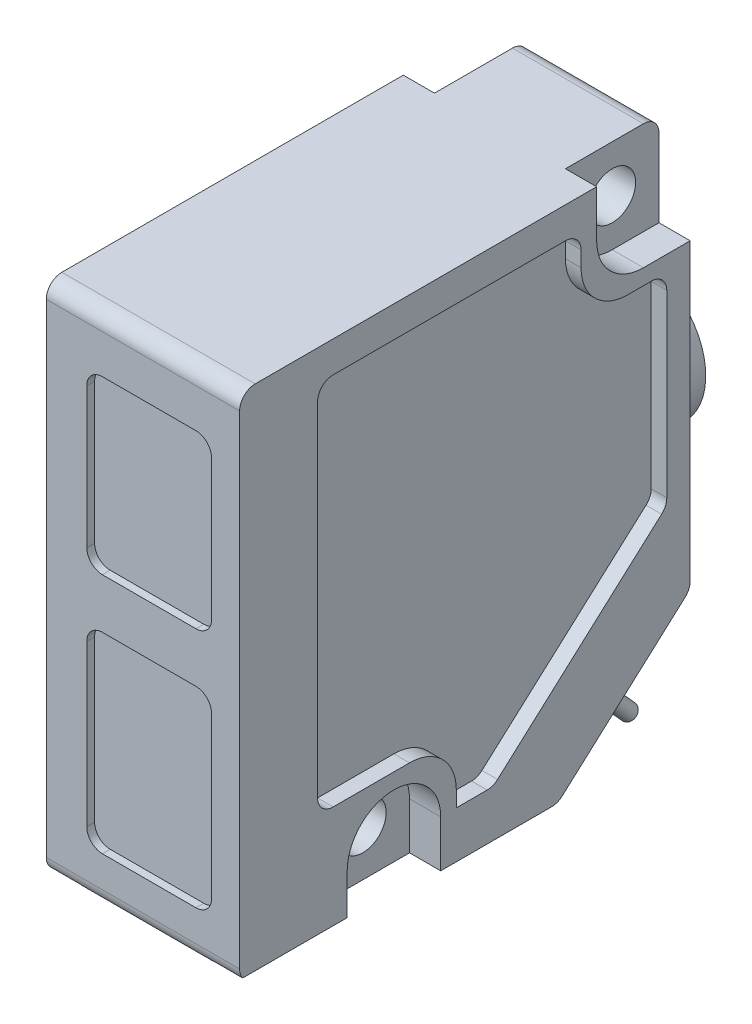
SolidWorks part; units mm, degrees
material "ABS"
ref_plane "Front Plane" through (0, 0, 0) normal (0, 0, 1) x (1, 0, 0)
ref_plane "Top Plane" through (0, 0, 0) normal (0, 1, 0) x (1, 0, 0)
ref_plane "Right Plane" through (0, 0, 0) normal (1, 0, 0) x (0, 0, -1)
sketch "Sketch1" plane through (0, 0, 0) normal (1, 0, 0) x (0, 0, -1)
  line L0 (1, 0) -> (27.9, 0)
  line L1 (28.9, -1) -> (28.9, -24.9046)
  line L2 (28.569, -25.6479) -> (20.6852, -32.7433)
  line L3 (20.0163, -33) -> (1, -33)
  line L4 (0, -32) -> (0, -1)
  arc A0 (1, -33) -> (0, -32) centre (1, -32) cw
  arc A1 (27.9, 0) -> (28.9, -1) centre (27.9, -1) cw
  arc A2 (1, 0) -> (0, -1) centre (1, -1) ccw
  arc A3 (28.9, -24.9046) -> (28.569, -25.6479) centre (27.9, -24.9046) cw
  arc A4 (20.6852, -32.7433) -> (20.0163, -33) centre (20.0163, -32) cw
  point P8 (0, -33)
  point P11 (28.9, 0)
  point P14 (0, 0)
  point P17 (28.9, -25.35)
  point P20 (20.4, -33)
  dimension "D5" = 1
  dimension "D6" = 1
  dimension "D1" = 33
  dimension "D2" = 28.9
  dimension "D3" = 20.4
  dimension "D4" = 7.65
extrude "Boss-Extrude1" add sketch "Sketch1" along normal blind 12.4
sketch "Sketch2" plane through (12.4, 0, 0) normal (1, 0, 0) x (0, 0, -1)
  line L0 (27.9, 0) -> (1, 0) construction
  line L1 (28.9, -24.9046) -> (28.9, -1) construction
  line L2 (1, -33) -> (20.0163, -33) construction
  line L3 (0, -1) -> (0, -32) construction
  circle A0 centre (25.9, -3) radius 1.5
  circle A1 centre (9.9, -30) radius 1.5
  dimension "D1" = 3
  dimension "D2" = 3
  dimension "D3" = 3
  dimension "D4" = 3
  dimension "D5" = 9.9
  dimension "D6" = 27
  dimension "D7" = 31.3847
  dimension "D8" = 16
extrude "Cut-Extrude1" cut sketch "Sketch2" against normal through all
sketch "Sketch3" plane through (12.4, 0, 0) normal (1, 0, 0) x (0, 0, -1)
  line L0 (27.9, 0) -> (1, 0) construction
  line L5 (6.9, -30) -> (6.9, -32.6022)
  line L6 (1, -33) -> (20.0163, -33) construction
  line L7 (12.9, -30) -> (12.9, -33)
  line L8 (6.9, -33) -> (12.9, -33)
  line L9 (22.9, 0) -> (28.9, 0)
  line L10 (22.9, 0) -> (22.9, -3)
  line L11 (25.9, -6) -> (28.9, -6)
  line L12 (28.9, 0) -> (28.9, -6)
  line L13 (28.9, -24.9046) -> (28.9, -1) construction
  line L15 (6.9, -33) -> (0, -33)
  line L17 (6.9, -32.6022) -> (0, -32.6022)
  line L18 (0, -33) -> (0, -32.6022)
  arc A1 (12.9, -30) -> (6.9, -30) centre (9.9, -30) ccw
  arc A2 (22.9, -3) -> (25.9, -6) centre (25.9, -3) ccw
  point P18 (22.9, -6)
  dimension "D3" = 3
  dimension "D4" = 6
  dimension "D1" = 6
  dimension "D2" = 6
  dimension "D5" = 0.3978
  dimension "D6" = 6.9
extrude "Cut-Extrude2" cut sketch "Sketch3" against normal blind 2
sketch "Sketch4" plane through (0, 0, 0) normal (-1, 0, 0) x (0, 0, 1)
  line L0 (-12.9, -30) -> (-12.9, -33)
  line L1 (-28.9, 0) -> (-22.9, 0)
  line L2 (-28.9, 0) -> (-28.9, -6)
  line L3 (-28.9, -6) -> (-25.9, -6)
  line L4 (-22.9, 0) -> (-22.9, -3)
  line L5 (-6.9, -30) -> (-6.9, -32.6)
  line L6 (-6.9, -33) -> (-12.9, -33)
  line L8 (-6.9, -33) -> (0, -33)
  line L10 (-6.9, -32.6) -> (0, -32.6)
  line L11 (0, -33) -> (0, -32.6)
  arc A0 (-25.9, -6) -> (-22.9, -3) centre (-25.9, -3) ccw
  arc A1 (-6.9, -30) -> (-12.9, -30) centre (-9.9, -30) ccw
  dimension "D3" = 3
  dimension "D4" = 6
  dimension "D1" = 6
  dimension "D2" = 6
  dimension "D5" = 0.4
  dimension "D6" = 6.9
extrude "Cut-Extrude3" cut sketch "Sketch4" against normal blind 2
sketch "Sketch5" plane through (12.4, 0, 0) normal (1, 0, 0) x (0, 0, -1)
  line L0 (5, -3) -> (5, -25)
  line L1 (6, -26) -> (10.9, -26)
  line L2 (13.9, -29) -> (13.9, -30)
  line L3 (13.9, -30) -> (15.8754, -30)
  line L4 (16.5443, -29.7433) -> (27.069, -20.2711)
  line L5 (27.4, -19.5278) -> (27.4, -8)
  line L6 (26.4, -7) -> (24.9, -7)
  line L7 (21.9, -4) -> (21.9, -3)
  line L8 (20.9, -2) -> (6, -2)
  line L9 (20.6852, -32.7433) -> (28.569, -25.6479) construction
  line L10 (28.9, -24.9046) -> (28.9, -6) construction
  line L11 (0, -1) -> (0, -32) construction
  line L12 (22.9, 0) -> (1, 0) construction
  line L15 (12.9, -33) -> (20.0163, -33) construction
  line L16 (22.9, 0) -> (1, 0) construction
  arc A0 (12.9, -30) -> (6.9, -30) centre (9.9, -30) ccw construction
  arc A1 (10.9, -26) -> (13.9, -29) centre (10.9, -29) cw
  arc A2 (24.9, -7) -> (21.9, -4) centre (24.9, -4) cw
  arc A3 (27.069, -20.2711) -> (27.4, -19.5278) centre (26.4, -19.5278) ccw
  arc A4 (21.9, -3) -> (20.9, -2) centre (20.9, -3) ccw
  arc A5 (27.4, -8) -> (26.4, -7) centre (26.4, -8) ccw
  arc A6 (15.8754, -30) -> (16.5443, -29.7433) centre (15.8754, -29) ccw
  arc A7 (5, -25) -> (6, -26) centre (6, -25) ccw
  arc A8 (5, -3) -> (6, -2) centre (6, -3) cw
  dimension "D10" = 3
  dimension "D11" = 1
  dimension "D1" = 1.5
  dimension "D2" = 5
  dimension "D3" = 2
  dimension "D4" = 7
  dimension "D6" = 4
  dimension "D7" = 1
  dimension "D8" = 3
  dimension "D9" = 5
extrude "Cut-Extrude4" cut sketch "Sketch5" against normal blind 1
sketch "Sketch6" plane through (0, 0, 0) normal (-1, 0, 0) x (0, 0, 1)
  line L0 (-6, -2) -> (-20.9, -2)
  line L1 (-21.9, -3) -> (-21.9, -4)
  line L2 (-24.9, -7) -> (-26.4, -7)
  line L3 (-27.4, -8) -> (-27.4, -19.5278)
  line L4 (-27.069, -20.2711) -> (-16.5443, -29.7433)
  line L5 (-15.8754, -30) -> (-13.9, -30)
  line L6 (-13.9, -30) -> (-13.9, -29)
  line L7 (-10.9, -26) -> (-6, -26)
  line L8 (-5, -25) -> (-5, -3)
  line L9 (0, -1) -> (0, -32) construction
  line L10 (-22.9, 0) -> (-1, 0) construction
  line L11 (-22.9, -3) -> (-22.9, 0) construction
  line L12 (-28.9, -6) -> (-25.9, -6) construction
  line L13 (-28.9, -24.9046) -> (-28.9, -6) construction
  line L14 (-20.6852, -32.7433) -> (-28.569, -25.6479) construction
  line L15 (-12.9, -33) -> (-20.0163, -33) construction
  line L16 (-12.9, -30) -> (-12.9, -33) construction
  arc A0 (-6.9, -30) -> (-12.9, -30) centre (-9.9, -30) ccw construction
  arc A1 (-6, -2) -> (-5, -3) centre (-6, -3) cw
  arc A2 (-6, -26) -> (-5, -25) centre (-6, -25) ccw
  arc A3 (-16.5443, -29.7433) -> (-15.8754, -30) centre (-15.8754, -29) ccw
  arc A4 (-27.4, -19.5278) -> (-27.069, -20.2711) centre (-26.4, -19.5278) ccw
  arc A5 (-26.4, -7) -> (-27.4, -8) centre (-26.4, -8) ccw
  arc A6 (-20.9, -2) -> (-21.9, -3) centre (-20.9, -3) ccw
  arc A7 (-13.9, -29) -> (-10.9, -26) centre (-10.9, -29) cw
  arc A8 (-21.9, -4) -> (-24.9, -7) centre (-24.9, -4) cw
  point P28 (-9.9, -27)
  dimension "D10" = 1
  dimension "D11" = 3
  dimension "D1" = 5
  dimension "D2" = 2
  dimension "D3" = 1
  dimension "D4" = 1
  dimension "D5" = 1.5
  dimension "D6" = 3
  dimension "D7" = 1
  dimension "D8" = 1
  dimension "D9" = 5
extrude "Cut-Extrude5" cut sketch "Sketch6" against normal blind 1
sketch "Sketch8" plane through (0, 0, 0) normal (0, 0, 1) x (1, 0, 0)
  line L0 (6.2, 1.1263) -> (6.2, -34.5812) construction
  line L1 (-4.8534, -10) -> (17.0259, -10) construction
  line L2 (-4.8534, -22.2) -> (17.0259, -22.2) construction
  line L3 (12.4, -1) -> (12.4, -32) construction
  line L4 (12.4, 0) -> (0, 0) construction
  line L5 (10.4, -33) -> (2, -33) construction
  line L6 (3.6, -3.5) -> (9.6, -3.5)
  line L7 (2.6, -4.5) -> (2.6, -13.5)
  line L8 (3.6, -14.5) -> (9.6, -14.5)
  line L9 (10.6, -4.5) -> (10.6, -13.5)
  line L10 (3.6, -17.7) -> (9.6, -17.7)
  line L11 (2.6, -18.7) -> (2.6, -29)
  line L12 (3.6, -30) -> (9.6, -30)
  line L13 (10.6, -18.7) -> (10.6, -29)
  arc A0 (9.6, -30) -> (10.6, -29) centre (9.6, -29) ccw
  arc A1 (2.6, -29) -> (3.6, -30) centre (3.6, -29) ccw
  arc A2 (9.6, -17.7) -> (10.6, -18.7) centre (9.6, -18.7) cw
  arc A3 (3.6, -17.7) -> (2.6, -18.7) centre (3.6, -18.7) ccw
  arc A4 (2.6, -13.5) -> (3.6, -14.5) centre (3.6, -13.5) ccw
  arc A5 (9.6, -14.5) -> (10.6, -13.5) centre (9.6, -13.5) ccw
  arc A6 (9.6, -3.5) -> (10.6, -4.5) centre (9.6, -4.5) cw
  arc A7 (3.6, -3.5) -> (2.6, -4.5) centre (3.6, -4.5) ccw
  point P24 (2.6, -30)
  point P27 (10.6, -17.7)
  point P30 (2.6, -17.7)
  point P33 (2.6, -14.5)
  point P38 (10.6, -3.5)
  point P41 (2.6, -3.5)
  dimension "D12" = 1
  dimension "D1" = 6.2
  dimension "D2" = 10
  dimension "D3" = 12.2
  dimension "D4" = 11
  dimension "D5" = 8
  dimension "D6" = 12.3
  dimension "D7" = 8
  dimension "D8" = 3.6
  dimension "D9" = 3.6
  dimension "D10" = 18.5
  dimension "D11" = 3
extrude "Cut-Extrude6" cut sketch "Sketch8" against normal blind 0.5
sketch "Sketch9" plane through (0, 0, -28.9) normal (0, 0, -1) x (-1, 0, 0)
  line L0 (-12.4, -24.9046) -> (-12.4, -6) construction
  line L1 (-10.4, 0) -> (-2, 0) construction
  circle A0 centre (-6.9, -15) radius 4.5
  dimension "D1" = 9
  dimension "D2" = 5.5
  dimension "D3" = 15
extrude "Boss-Extrude2" add sketch "Sketch9" along normal blind 0.5
sketch "Sketch10" plane through (0, 0, -29.4) normal (0, 0, -1) x (-1, 0, 0)
  circle A0 centre (-6.9, -15) radius 4.25
  dimension "D1" = 8.5
extrude "Boss-Extrude3" add sketch "Sketch10" along normal blind 0.5
sketch "Sketch11" plane through (0, 0, -29.9) normal (0, 0, -1) x (-1, 0, 0)
  circle A0 centre (-6.9, -15) radius 4.5
extrude "Boss-Extrude4" add sketch "Sketch11" along normal blind 1
sketch "Sketch12" plane through (0, -28.3757, -25.5381) normal (0, -0.7433, -0.669) x (1, 0, 0)
  line L2 (12.4, -4.0776) -> (0, 6.5289) construction
  line L3 (12.4, 6.5289) -> (0, -4.0776) construction
  circle A1 centre (6.2, 1.2257) radius 3
  point P4 (6.2, 1.2257)
  dimension "D1" = 6
extrude "Boss-Extrude5" add sketch "Sketch12" along normal blind 1
sketch "Sketch13" plane through (0, -29.119, -26.2071) normal (0, -0.7433, -0.669) x (1, 0, 0)
  circle A0 centre (6.2, 1.2257) radius 2
  dimension "D1" = 4
extrude "Boss-Extrude6" add sketch "Sketch13" along normal blind 3
sketch "Sketch14" plane through (0, -31.3489, -28.214) normal (0, -0.7433, -0.669) x (1, 0, 0)
  line L0 (8.2, 1.2257) -> (4.2, 1.2257) construction
  circle A0 centre (6.2, 1.2257) radius 2 construction
  arc A1 (6.21, 1.1262) -> (6.21, 1.3252) centre (6.7, 1.2257) ccw
  arc A2 (6.21, 1.3252) -> (6.21, 1.1262) centre (5.72, 1.2257) ccw
  point P9 (6.2, 1.2257)
  dimension "D1" = 1
  dimension "D2" = 1
  dimension "D3" = 0.48
  dimension "D4" = 0.98
extrude "Boss-Extrude7" add sketch "Sketch14" along normal blind 5
